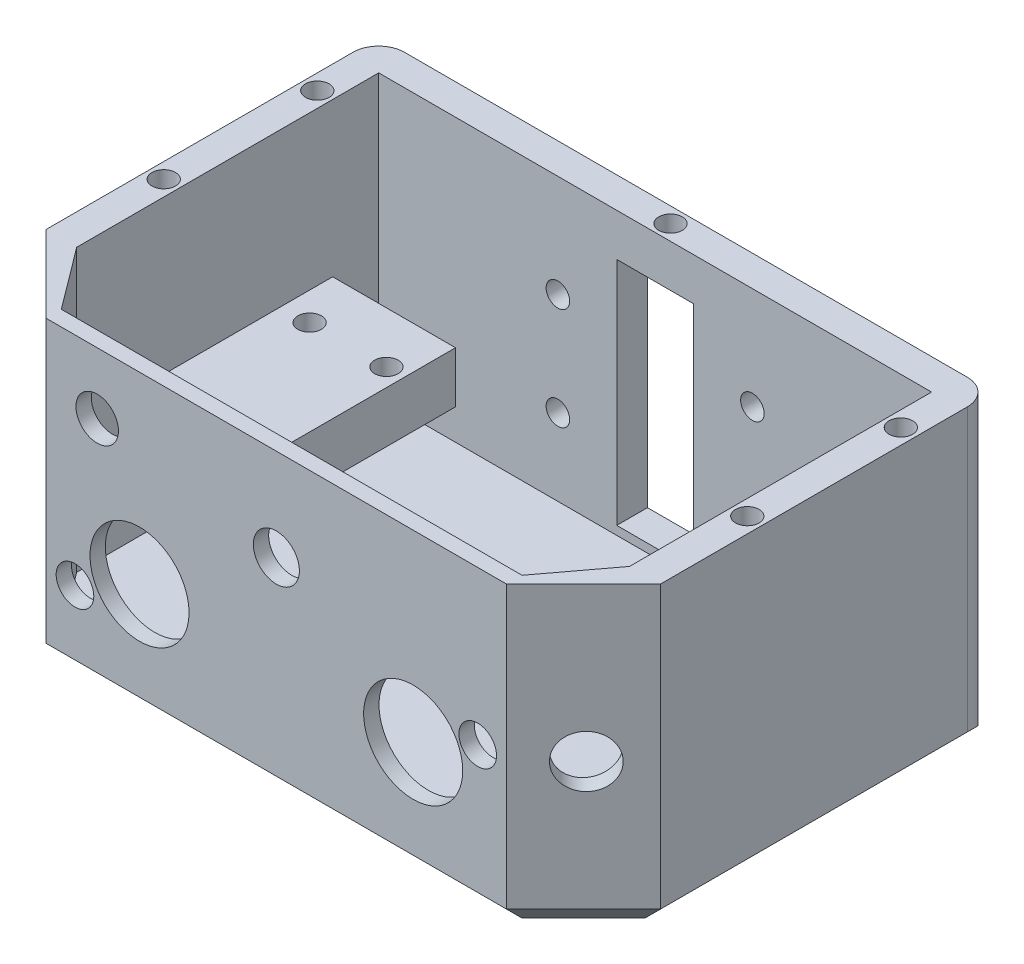
SolidWorks part; units mm, degrees
ref_plane "Plan de face" through (0, 0, 0) normal (0, 0, 1) x (1, 0, 0)
ref_plane "Plan de dessus" through (0, 0, 0) normal (0, 1, 0) x (1, 0, 0)
ref_plane "Plan de droite" through (0, 0, 0) normal (1, 0, 0) x (0, 0, -1)
sketch "Esquisse1" plane through (0, 0, 0) normal (0, 0, 1) x (1, 0, 0)
  line L1 (-60, -30) -> (60, -30)
  line L2 (-60, -30) -> (-60, 30)
  line L3 (-60, 30) -> (60, 30)
  line L4 (60, -30) -> (60, 30)
  line L5 (-60, -30) -> (60, 30) construction
  line L6 (-60, 30) -> (60, -30) construction
  point P0 (0, 0)
  dimension "D1" = 120
  dimension "D2" = 60
extrude "Boss.-Extru.1" add sketch "Esquisse1" against normal blind 80
chamfer "Chanfrein1" distance 15 angle 45 1 edges at (60, 0, 0)
chamfer "Chanfrein2" distance 15 angle 45 1 edges at (-60, 0, 0)
sketch "Esquisse2" plane through (0, 30, 0) normal (0, 1, 0) x (1, 0, 0)
  line L0 (-54, 15) -> (-54, 74)
  line L1 (-45, 3) -> (45, 3)
  line L2 (54, 15) -> (54, 74)
  line L3 (60, 15) -> (54, 15) construction
  line L4 (45, 0) -> (45, 3) construction
  line L5 (-45, 0) -> (-45, 3) construction
  line L6 (45, 0) -> (-45, 0) construction
  line L7 (-60, 15) -> (-54, 15) construction
  line L8 (45, 3) -> (54, 15)
  line L9 (-45, 3) -> (-54, 15)
  line L10 (-54, 74) -> (54, 74)
  line L11 (60, 80) -> (-60, 80) construction
  dimension "D1" = 6
  dimension "D2" = 6
  dimension "D3" = 3
  dimension "D4" = 3
  dimension "D5" = 6
extrude "Enlèv. mat.-Extru.1" cut sketch "Esquisse2" against normal blind 55
sketch "Esquisse3" plane through (0, 0, 0) normal (0, 0, 1) x (1, 0, 0)
  line L0 (45, 30) -> (-45, 30) construction
  line L1 (45, -30) -> (45, 30) construction
  line L2 (-45, -30) -> (45, -30) construction
  line L3 (-45, 30) -> (-45, -30) construction
  circle A0 centre (0, 12) radius 4.5
  circle A1 centre (-35, 18) radius 4.15
  circle A2 centre (26.73, -5.87) radius 9.675
  circle A3 centre (-26.73, -5.87) radius 9.675
  circle A5 centre (39.34, 0) radius 3.675
  circle A6 centre (-39.34, -12.37) radius 3.675
  point P0 (0, 0)
  dimension "D3" = 9
  dimension "D4" = 8.3
  dimension "D5" = 19.35
  dimension "D6" = 7.35
  dimension "D8" = 19.35
  dimension "D19" = 7.35
  dimension "D1" = 18
  dimension "D2" = 45
  dimension "D9" = 5.66
  dimension "D10" = 18.27
  dimension "D11" = 24.13
  dimension "D12" = 18.27
  dimension "D13" = 24.13
  dimension "D14" = 12
  dimension "D15" = 10
  dimension "D18" = 30
  dimension "D20" = 5.66
  dimension "D21" = 6.5
extrude "Enlèv. mat.-Extru.2" cut sketch "Esquisse3" against normal blind 10
sketch "Esquisse4" plane through (22.5, 0, 22.5) normal (0.7071, 0, 0.7071) x (0.7071, 0, -0.7071)
  line L0 (31.8198, -30) -> (31.8198, 30) construction
  line L1 (31.8198, 30) -> (53.033, 30) construction
  circle A0 centre (42.8198, 0) radius 5.1
  dimension "D1" = 10.2
  dimension "D2" = 11
  dimension "D3" = 30
extrude "Enlèv. mat.-Extru.3" cut sketch "Esquisse4" against normal blind 10
sketch "Esquisse5" plane through (-22.5, 0, 22.5) normal (-0.7071, 0, 0.7071) x (0.7071, 0, 0.7071)
  line L1 (-53.033, 30) -> (-31.8198, 30) construction
  line L2 (-31.8198, 30) -> (-31.8198, -30) construction
  circle A0 centre (-42.8198, 0) radius 5.1
  dimension "D1" = 10.2
  dimension "D2" = 11
  dimension "D3" = 30
extrude "Enlèv. mat.-Extru.4" cut sketch "Esquisse5" against normal blind 10
chamfer "Chanfrein3" distance 5 angle 45 5 edges at (60, -30, -47.5) (52.5, -30, -7.5) (-60, -30, -47.5) (-52.5, -30, -7.5) (0, -30, 0)
sketch "Esquisse7" plane through (0, 0, -80) normal (0, 0, -1) x (-1, 0, 0)
  line L0 (-60, 30) -> (60, 30) construction
  line L1 (-7.5, -23.31) -> (7.5, -23.31)
  line L2 (-7.5, -23.31) -> (-7.5, 21.69)
  line L3 (-7.5, 21.69) -> (7.5, 21.69)
  line L4 (7.5, -23.31) -> (7.5, 21.69)
  line L5 (60, 30) -> (60, -25) construction
  dimension "D1" = 8.31
  dimension "D2" = 52.5
  dimension "D3" = 15
  dimension "D4" = 45
extrude "Enlèv. mat.-Extru.5" cut sketch "Esquisse7" against normal blind 15
chamfer "Chanfrein5" distance 5 angle 45 1 edges at (0, -30, -80)
sketch "Esquisse8" plane through (0, 0, 0) normal (0, 0, 1) x (1, 0, 0)
  line L2 (45, -25) -> (45, 30) construction
  line L4 (45, 30) -> (-45, 30) construction
  line L7 (-12.5, 25) -> (12.5, 25)
  line L8 (-12.5, 25) -> (-12.5, 23)
  line L9 (-12.5, 23) -> (12.5, 23)
  line L10 (12.5, 25) -> (12.5, 23)
  line L11 (-12.5, 25) -> (12.5, 23) construction
  line L12 (-12.5, 23) -> (12.5, 25) construction
  point P8 (0, 0)
  point P14 (0, 24)
  point P19 (-9.5, -26)
  point P24 (9.5, -26)
  dimension "D16" = 2
  dimension "D17" = 25
  dimension "D23" = 5
  dimension "D24" = 32.5
extrude "Boss.-Extru.2" add sketch "Esquisse8" against normal blind 6
sketch "Esquisse10" plane through (60, 0, 0) normal (1, 0, 0) x (0, 0, -1)
  line L0 (15, 30) -> (15, -25) construction
  line L1 (25, -10) -> (65, -10)
  line L2 (25, -10) -> (25, 0)
  line L3 (25, 0) -> (65, 0)
  line L4 (65, -10) -> (65, 0)
  line L5 (25, -10) -> (65, 0) construction
  line L6 (25, 0) -> (65, -10) construction
  line L7 (15, -25) -> (80, -25) construction
  point P0 (45, -5)
  dimension "D1" = 10
  dimension "D2" = 40
  dimension "D3" = 15
  dimension "D4" = 10
extrude "Boss.-Extru.4" add sketch "Esquisse10" against normal blind 30
sketch "Esquisse11" plane through (-60, 0, 0) normal (-1, 0, 0) x (0, 0, 1)
  line L0 (-80, -25) -> (-15, -25) construction
  line L1 (-65, 0) -> (-25, 0)
  line L2 (-65, 0) -> (-65, -10)
  line L3 (-65, -10) -> (-25, -10)
  line L4 (-25, 0) -> (-25, -10)
  line L5 (-65, 0) -> (-25, -10) construction
  line L6 (-65, -10) -> (-25, 0) construction
  line L7 (-15, -25) -> (-15, 30) construction
  point P0 (-45, -5)
  dimension "D1" = 10
  dimension "D2" = 15
  dimension "D3" = 10
  dimension "D4" = 40
extrude "Boss.-Extru.5" add sketch "Esquisse11" against normal blind 30
sketch "Esquisse12" plane through (0, 0, 0) normal (0, 1, 0) x (1, 0, 0)
  line L1 (30, 65) -> (30, 25) construction
  line L2 (30, 65) -> (54, 65) construction
  line L3 (54, 65) -> (54, 25) construction
  line L4 (-30, 25) -> (-30, 65) construction
  line L5 (-30, 65) -> (-54, 65) construction
  line L6 (-54, 25) -> (-54, 65) construction
  circle A0 centre (33.5, 55) radius 2.3
  circle A1 centre (48.5, 55) radius 2.3
  circle A2 centre (-33.5, 55) radius 2.3
  circle A3 centre (-48.5, 55) radius 2.3
  dimension "D4" = 4.6
  dimension "D5" = 4.6
  dimension "D7" = 4.6
  dimension "D8" = 4.6
  dimension "D1" = 3.5
  dimension "D2" = 15
  dimension "D3" = 10
  dimension "D6" = 5.5
  dimension "D9" = 3.5
  dimension "D10" = 15
  dimension "D11" = 10
  dimension "D12" = 5.5
extrude "Enlèv. mat.-Extru.7" cut sketch "Esquisse12" against normal blind 15
sketch "Esquisse13" plane through (0, 30, 0) normal (0, 1, 0) x (1, 0, 0)
  line L0 (-54, 74) -> (-54, 15) construction
  line L1 (54, 15) -> (54, 74) construction
  line L2 (60, 80) -> (-60, 80) construction
  line L3 (60, 80) -> (60, 15) construction
  circle A0 centre (-57, 65) radius 2.3
  circle A1 centre (-57, 35) radius 2.3
  circle A2 centre (57, 65) radius 2.3
  circle A3 centre (57, 35) radius 2.3
  circle A4 centre (0, 77) radius 2.3
  dimension "D6" = 4.6
  dimension "D7" = 4.6
  dimension "D8" = 4.6
  dimension "D9" = 4.6
  dimension "D10" = 4.6
  dimension "D1" = 3
  dimension "D2" = 3
  dimension "D3" = 3
  dimension "D4" = 3
  dimension "D5" = 3
  dimension "D11" = 15
  dimension "D12" = 30
  dimension "D13" = 15
  dimension "D14" = 30
  dimension "D15" = 60
extrude "Enlèv. mat.-Extru.8" cut sketch "Esquisse13" against normal blind 16
sketch "Esquisse14" plane through (0, 0, -80) normal (0, 0, -1) x (-1, 0, 0)
  line L3 (55, -30) -> (-55, -30) construction
  line L4 (-7.5, 21.69) -> (-7.5, -23.31) construction
  line L5 (7.5, -23.31) -> (7.5, 21.69) construction
  circle A0 centre (19, 10) radius 2.3
  circle A1 centre (19, -10) radius 2.3
  circle A2 centre (-19, -10) radius 2.3
  circle A3 centre (-19, 10) radius 2.3
  dimension "D1" = 4.6
  dimension "D2" = 4.6
  dimension "D3" = 4.6
  dimension "D4" = 4.6
  dimension "D5" = 20
  dimension "D6" = 20
  dimension "D7" = 20
  dimension "D8" = 20
  dimension "D9" = 11.5
  dimension "D10" = 11.5
  dimension "D11" = 11.5
  dimension "D12" = 11.5
extrude "Enlèv. mat.-Extru.9" cut sketch "Esquisse14" against normal blind 10
sketch "Esquisse15" plane through (0, 0, -3) normal (0, 0, -1) x (-1, 0, 0)
  line L0 (-12.5, 25) -> (12.5, 25) construction
  line L1 (45, 30) -> (45, -25) construction
  line L2 (-45, -25) -> (-45, 30) construction
  circle A0 centre (17, 11) radius 3.2
  circle A1 centre (-17, 11) radius 3.25
  dimension "D1" = 6.4
  dimension "D2" = 6.5
  dimension "D3" = 14
  dimension "D4" = 14
  dimension "D5" = 28
  dimension "D6" = 28
extrude "Boss.-Extru.6" add sketch "Esquisse15" along normal blind 3.4
sketch "Esquisse16" plane through (0, 0, -6.4) normal (0, 0, -1) x (-1, 0, 0)
  circle A0 centre (17, 11) radius 2.3
  circle A1 centre (-17, 11) radius 2.3
  dimension "D1" = 4.6
  dimension "D2" = 4.6
extrude "Enlèv. mat.-Extru.10" cut sketch "Esquisse16" against normal blind 5
sketch "Esquisse18" plane through (0, -25, 0) normal (0, 1, 0) x (1, 0, 0)
  line L0 (-45, 3) -> (-45, 14.8192) construction
  line L1 (45, 3) -> (45, 14.8192) construction
  line L2 (-7.5, 15) -> (-7.5, 3)
  line L4 (-7.5, 15) -> (7.5, 15)
  line L5 (-7.5, 3) -> (7.5, 3)
  line L8 (7.5, 3) -> (7.5, 15)
  line L9 (-45, 3) -> (45, 3) construction
  line L10 (-7.5, 42) -> (7.5, 42)
  line L11 (-7.5, 42) -> (-7.5, 30)
  line L12 (-7.5, 30) -> (7.5, 30)
  line L13 (7.5, 42) -> (7.5, 30)
  line L14 (-7.5, 42) -> (7.5, 30) construction
  line L15 (-7.5, 30) -> (7.5, 42) construction
  point P9 (0, 36)
  dimension "D1" = 37.5
  dimension "D2" = 37.5
  dimension "D3" = 0
  dimension "D4" = 12
  dimension "D5" = 15
  dimension "D6" = 12
  dimension "D7" = 15
  dimension "D8" = 37.5
extrude "Enlèv. mat.-Extru.13" cut sketch "Esquisse18" against normal blind 9
fillet "Congé1" radius 5 2 edges at (60, 2.5, -80) (-60, 2.5, -80)
